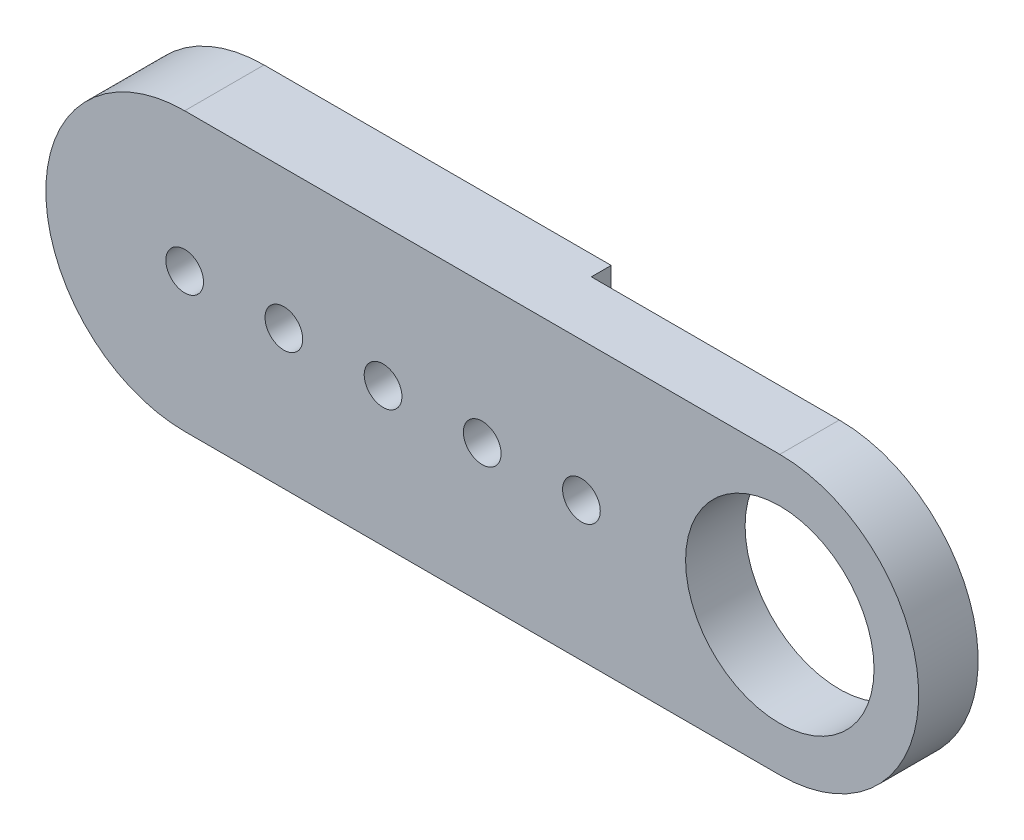
SolidWorks part; units mm, degrees
ref_plane "Plan de face" through (0, 0, 0) normal (0, 0, 1) x (1, 0, 0)
ref_plane "Plan de dessus" through (0, 0, 0) normal (0, 1, 0) x (1, 0, 0)
ref_plane "Plan de droite" through (0, 0, 0) normal (1, 0, 0) x (0, 0, -1)
sketch "Esquisse1" plane through (0, 0, 0) normal (0, 0, 1) x (1, 0, 0)
  line L0 (0, -30.579) -> (0, 34.1828) construction
  line L1 (0, 14) -> (-60, 14)
  line L2 (0, -14) -> (-60, -14)
  line L3 (0, 0) -> (-125.3395, 0) construction
  circle A0 centre (0, 0) radius 9.5
  arc A1 (0, 14) -> (0, -14) centre (0, 0) cw
  arc A2 (-60, 14) -> (-60, -14) centre (-60, 0) ccw
  circle A3 centre (-60, 0) radius 1.9
  circle A4 centre (-50, 0) radius 1.9
  circle A5 centre (-40, 0) radius 1.9
  circle A6 centre (-30, 0) radius 1.9
  circle A7 centre (-20, 0) radius 1.9
  dimension "D1" = 19
  dimension "D2" = 14
  dimension "D4" = 3.8
  dimension "D3" = 60
  dimension "D5" = 5
extrude "Boss.-Extru.1" add sketch "Esquisse1" along normal blind 8
sketch "Esquisse3" plane through (0, 0, 0) normal (0, 0, -1) x (-1, 0, 0)
  line L0 (60, -14) -> (0, -14) construction
  line L1 (25, -14) -> (-14, -14)
  line L2 (25, -14) -> (25, 14)
  line L3 (25, 14) -> (-14, 14)
  line L4 (-14, -14) -> (-14, 14)
  line L5 (0, 14) -> (60, 14) construction
  arc A0 (0, 14) -> (0, -14) centre (0, 0) ccw construction
  dimension "D1" = 25
extrude "Enlèv. mat.-Extru.1" cut sketch "Esquisse3" against normal blind 2
